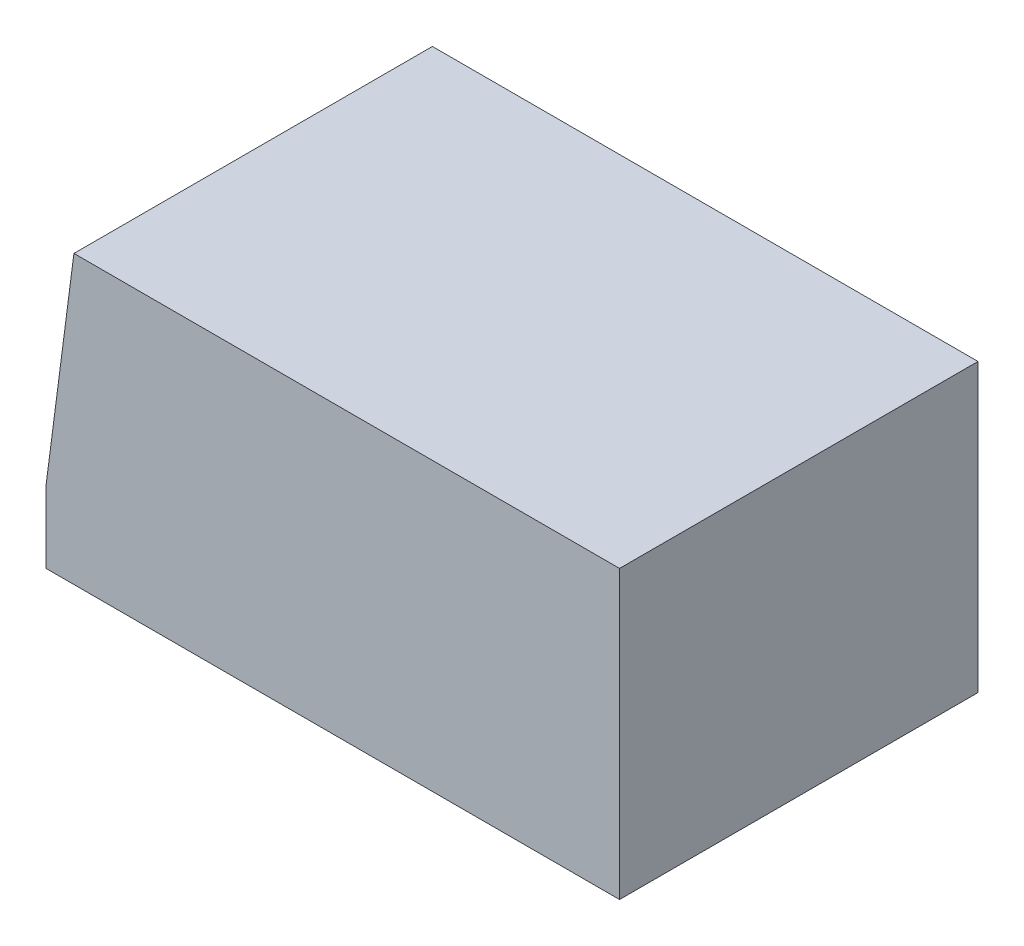
SolidWorks part; units mm, degrees
ref_plane "Plan de face" through (0, 0, 0) normal (0, 0, 1) x (1, 0, 0)
ref_plane "Plan de dessus" through (0, 0, 0) normal (0, 1, 0) x (1, 0, 0)
ref_plane "Plan de droite" through (0, 0, 0) normal (1, 0, 0) x (0, 0, -1)
sketch "Esquisse1" plane through (0, 0, 0) normal (0, 1, 0) x (1, 0, 0)
  line L1 (-40, -25) -> (40, -25)
  line L2 (-40, -25) -> (-40, 25)
  line L3 (-40, 25) -> (40, 25)
  line L4 (40, -25) -> (40, 25)
  line L5 (-40, -25) -> (40, 25) construction
  line L6 (-40, 25) -> (40, -25) construction
  point P0 (0, 0)
  dimension "D1" = 50
  dimension "D2" = 80
extrude "Boss.-Extru.1" add sketch "Esquisse1" along normal blind 40
chamfer "Chanfrein1" distance 30 angle 7.4 1 edges at (-40, 40, 0)
sketch "Esquisse2" plane through (-40.6137, 5.2748, 0) normal (-0.9917, 0.1288, 0) x (0, 0, 1)
  circle A0 centre (0, 18.9126) radius 12.5
  point P2 (0, 0)
  dimension "D1" = 25
extrude "Enlèv. mat.-Extru.1" cut sketch "Esquisse2" against normal blind 40
